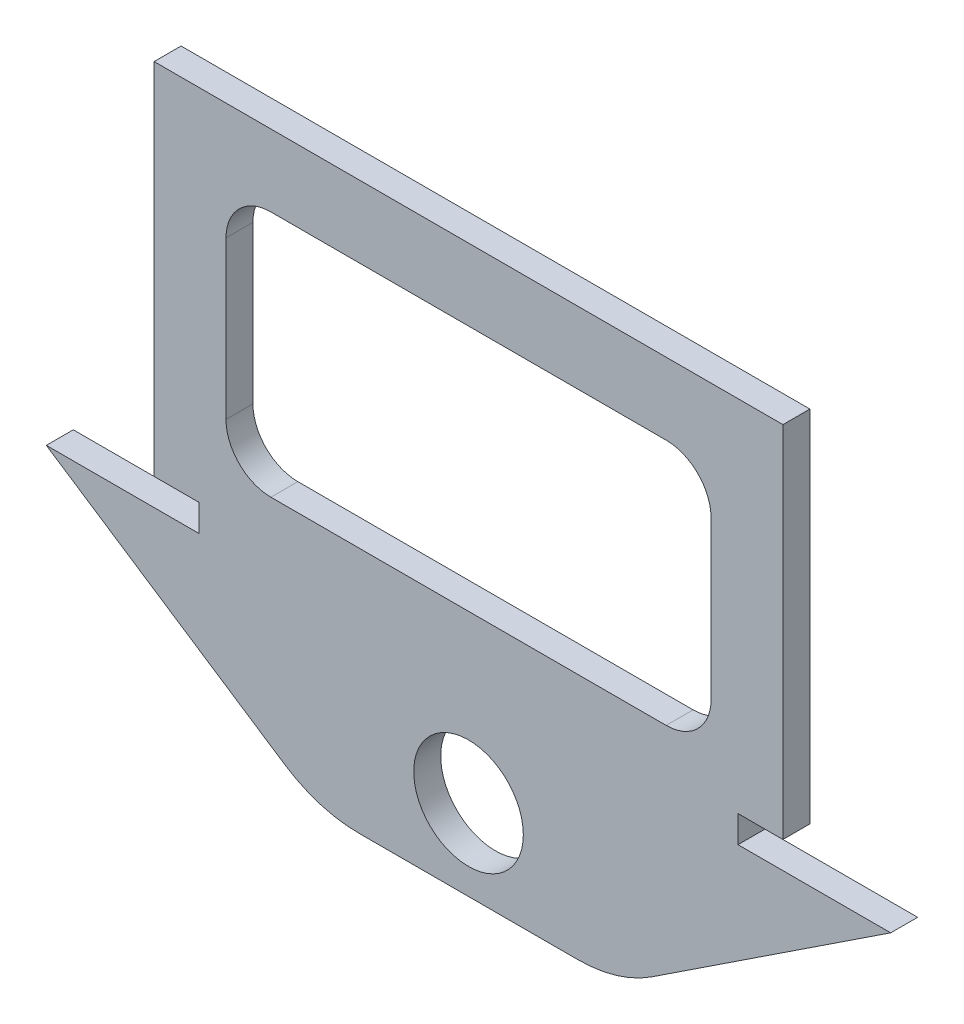
SolidWorks part; units mm, degrees
material "MDF"
ref_plane "Plano frontal" through (0, 0, 0) normal (0, 0, 1) x (1, 0, 0)
ref_plane "Plano superior" through (0, 0, 0) normal (0, 1, 0) x (1, 0, 0)
ref_plane "Plano direito" through (0, 0, 0) normal (1, 0, 0) x (0, 0, -1)
sketch "Esboço1" plane through (0, 0, 0) normal (0, 0, 1) x (1, 0, 0)
  line L0 (0, 99.3199) -> (0, -99.3199) construction
  line L1 (0, 0) -> (-94, 0) construction
  line L2 (-94, 0) -> (-60, 0)
  line L3 (-60, 0) -> (-60, 6)
  line L4 (54, 60) -> (54, 25)
  line L5 (-70, 6) -> (-70, 86)
  line L6 (-24.3453, -40) -> (24.3453, -40)
  line L7 (-70, 86) -> (70, 86)
  line L8 (60, 6) -> (70, 6)
  line L9 (-94, 0) -> (-40.8617, -35.0442)
  line L10 (-60, 6) -> (-70, 6)
  line L11 (-44, 70) -> (44, 70)
  line L12 (-54, 60) -> (-54, 25)
  line L13 (-44, 15) -> (44, 15)
  line L14 (94, 0) -> (40.8617, -35.0442)
  line L15 (70, 6) -> (70, 86)
  line L16 (60, 0) -> (60, 6)
  line L17 (94, 0) -> (60, 0)
  arc A0 (-40.8617, -35.0442) -> (-24.3453, -40) centre (-24.3453, -10) ccw
  arc A1 (-44, 70) -> (-54, 60) centre (-44, 60) ccw
  arc A2 (-54, 25) -> (-44, 15) centre (-44, 25) ccw
  arc A3 (54, 25) -> (44, 15) centre (44, 25) cw
  arc A4 (44, 70) -> (54, 60) centre (44, 60) cw
  arc A5 (40.8617, -35.0442) -> (24.3453, -40) centre (24.3453, -10) cw
  circle A7 centre (0, -22) radius 12.2
  point P12 (0, -40)
  point P20 (0, 70)
  point P32 (0, 15)
  point P36 (0, 86)
  dimension "D1" = 30
  dimension "D2" = 80
  dimension "D4" = 10
  dimension "D9" = 24.4
  dimension "D12" = 22
  dimension "D3" = 60
  dimension "D5" = 40
  dimension "D6" = 34
  dimension "D7" = 10
  dimension "D8" = 6
  dimension "D10" = 16
  dimension "D11" = 16
extrude "Ressalto-extrusão1" add sketch "Esboço1" along normal blind 6
